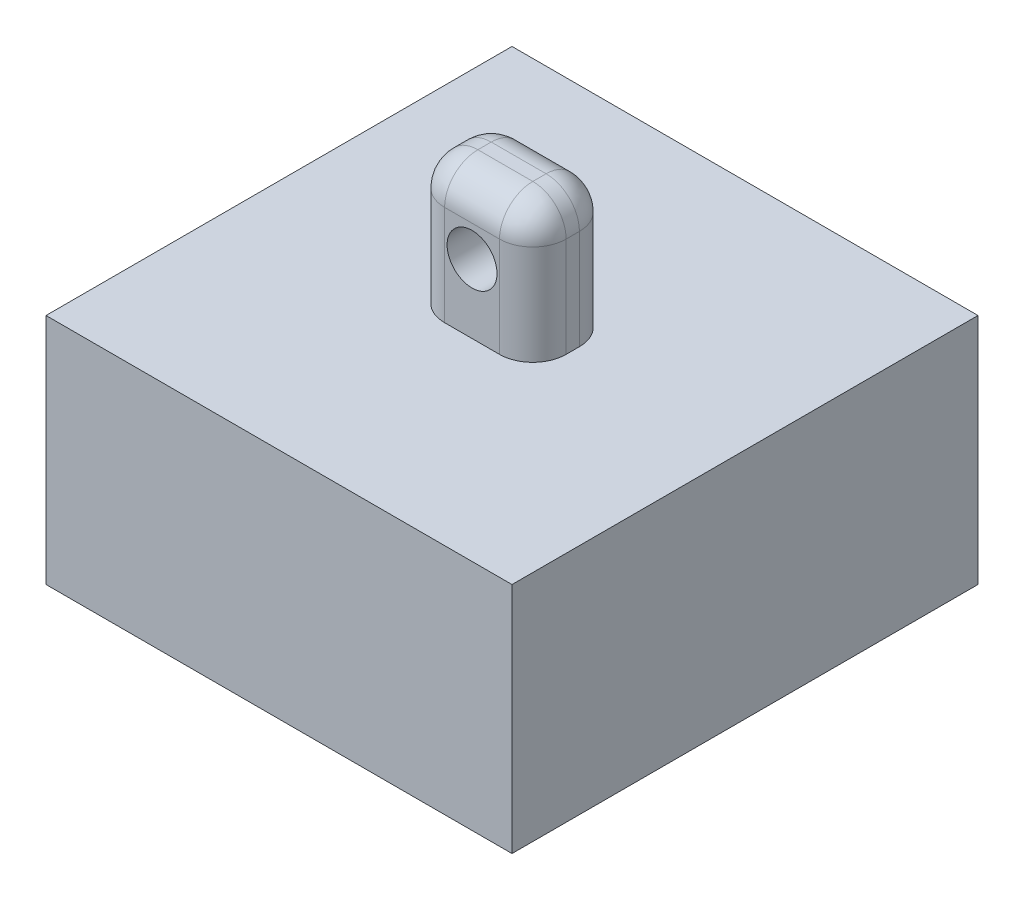
SolidWorks part; units mm, degrees
ref_plane "Front Plane" through (0, 0, 0) normal (0, 0, 1) x (1, 0, 0)
ref_plane "Top Plane" through (0, 0, 0) normal (0, 1, 0) x (1, 0, 0)
ref_plane "Right Plane" through (0, 0, 0) normal (1, 0, 0) x (0, 0, -1)
sketch "Sketch1" plane through (0, 0, 0) normal (0, 1, 0) x (1, 0, 0)
  line L1 (-10.5, -10.5) -> (10.5, -10.5)
  line L2 (-10.5, -10.5) -> (-10.5, 10.5)
  line L3 (-10.5, 10.5) -> (10.5, 10.5)
  line L4 (10.5, -10.5) -> (10.5, 10.5)
  line L5 (-10.5, -10.5) -> (10.5, 10.5) construction
  line L6 (-10.5, 10.5) -> (10.5, -10.5) construction
  line L7 (-14, -14) -> (14, -14)
  line L8 (-14, -14) -> (-14, 14)
  line L9 (-14, 14) -> (14, 14)
  line L10 (14, -14) -> (14, 14)
  line L11 (-14, -14) -> (14, 14) construction
  line L12 (-14, 14) -> (14, -14) construction
  point P0 (0, 0)
  point P6 (0, 0)
  dimension "D1" = 21
  dimension "D2" = 21
  dimension "D3" = 28
  dimension "D4" = 28
extrude "Boss-Extrude1" add sketch "Sketch1" along normal blind 11
sketch "Sketch2" plane through (0, 11, 0) normal (0, 1, 0) x (1, 0, 0)
  line L8 (14, -14) -> (14, 14)
  line L9 (14, 14) -> (-14, 14)
  line L10 (-14, 14) -> (-14, -14)
  line L11 (-14, -14) -> (14, -14)
  line L12 (14, -14) -> (14, 14)
  line L13 (14, 14) -> (-14, 14)
  line L14 (-14, 14) -> (-14, -14)
  line L15 (-14, -14) -> (14, -14)
  dimension "D1" = 0
extrude "Boss-Extrude2" add sketch "Sketch2" along normal blind 3
sketch "Sketch3" plane through (0, 14, 0) normal (0, 1, 0) x (1, 0, 0)
  line L0 (-14, 14) -> (14, -14) construction
  line L2 (3.65, -2.4) -> (-3.65, -2.4)
  line L3 (3.65, -2.4) -> (3.65, 2.4)
  line L4 (3.65, 2.4) -> (-3.65, 2.4)
  line L5 (-3.65, -2.4) -> (-3.65, 2.4)
  line L6 (3.65, -2.4) -> (-3.65, 2.4) construction
  line L7 (3.65, 2.4) -> (-3.65, -2.4) construction
  point P4 (0, 0)
  point P9 (0, -0.8315)
  point P10 (0.4897, -0.4897)
  dimension "D1" = 4.8
  dimension "D2" = 7.3
extrude "Boss-Extrude3" add sketch "Sketch3" along normal blind 8
fillet "Fillet3" radius 2 8 edges at (-3.65, 18, 2.4) (-3.65, 18, -2.4) (-3.65, 22, 0) (0, 22, -2.4) (0, 22, 2.4) (3.65, 18, 2.4) (3.65, 18, -2.4) (3.65, 22, 0)
sketch "Sketch4" plane through (0, 0, -2.4) normal (0, 0, -1) x (-1, 0, 0)
  circle A0 centre (0, 18.1286) radius 1.5
  dimension "D1" = 3
extrude "Cut-Extrude1" cut sketch "Sketch4" against normal blind 5
